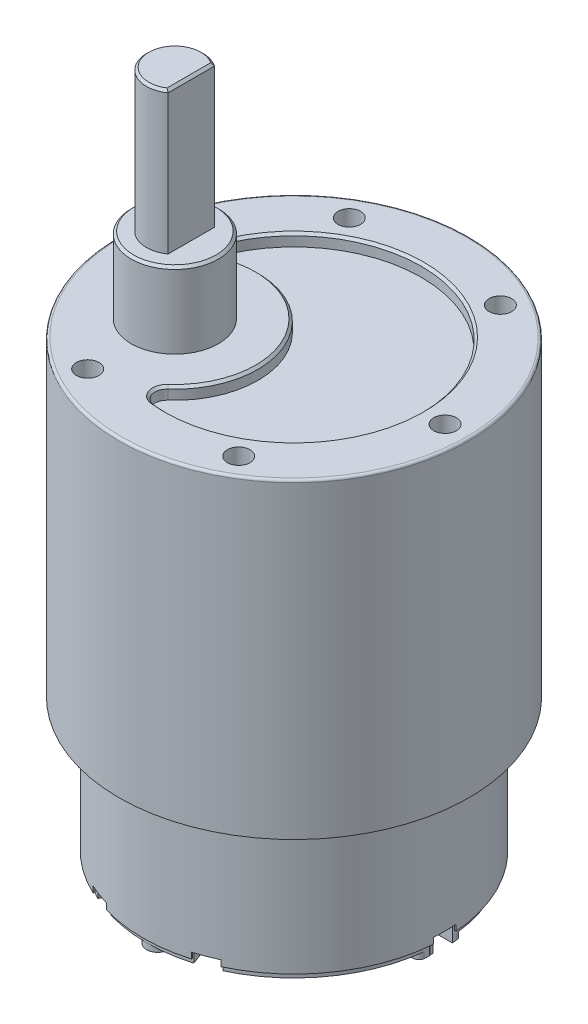
SolidWorks part; units mm, degrees
ref_plane "Front Plane" through (0, 0, 0) normal (0, 0, 1) x (1, 0, 0)
ref_plane "Top Plane" through (0, 0, 0) normal (0, 1, 0) x (1, 0, 0)
ref_plane "Right Plane" through (0, 0, 0) normal (1, 0, 0) x (0, 0, -1)
sketch "Sketch1" plane through (0, 0, 0) normal (0, 1, 0) x (1, 0, 0)
  circle A0 centre (0, 0) radius 18.5
extrude "Boss-Extrude1" add sketch "Sketch1" along normal blind 47
sketch "Sketch2" plane through (0, 0, 0) normal (0, -1, 0) x (1, 0, 0)
  circle A0 centre (0, 0) radius 15.9723
extrude "Cut-Extrude1" cut sketch "Sketch2" against normal blind 14.1 flip side to cut
sketch "Sketch3" plane through (0, 47, 0) normal (0, 1, 0) x (1, 0, 0)
  line L0 (0, 0) -> (0, 50000) construction
  line L1 (0, 0) -> (-50000, 0) construction
  circle A0 centre (-7.98, 13.8218) radius 1.1938
  circle A1 centre (-15.96, 0) radius 1.1938
  circle A2 centre (0, 0) radius 15.96
  circle A3 centre (0, 0) radius 15.96 construction
  circle A4 centre (7.98, 13.8218) radius 1.1938
  circle A5 centre (15.96, 0) radius 1.1938
  circle A6 centre (7.98, -13.8218) radius 1.1938
  circle A7 centre (-7.98, -13.8218) radius 1.1938
  point P21 (0, 0)
  dimension "D2" = 6
  dimension "D1" = 2.54
sketch "Sketch4" plane through (0, 47, 0) normal (0, 1, 0) x (1, 0, 0)
  line L0 (-7.98, 13.8218) -> (-7.98, -13.8218) construction
  line L1 (-15.96, 0) -> (-7.98, -13.8218) construction
  line L2 (-11.97, -6.9109) -> (17.6689, 10.2011) construction
  circle A0 centre (-7.98, -4.6073) radius 4.6073
extrude "Boss-Extrude2" add sketch "Sketch4" along normal blind 8
sketch "Sketch5" plane through (0, 55, 0) normal (0, 1, 0) x (1, 0, 0)
  circle A0 centre (-7.98, -4.6073) radius 3
  circle A2 centre (-7.98, -4.6073) radius 4.6073 construction
extrude "Boss-Extrude3" add sketch "Sketch5" along normal blind 15
sketch "Sketch6" plane through (0, 70, 0) normal (0, 1, 0) x (1, 0, 0)
  line L0 (-6.2443, -2.1603) -> (-6.2443, -7.0542)
  circle A0 centre (-7.98, -4.6073) radius 3 construction
  arc A1 (-6.2443, -2.1603) -> (-6.2443, -7.0542) centre (-7.98, -4.6073) ccw
extrude "Cut-Extrude3" cut sketch "Sketch6" against normal blind 15 flip side to cut
sketch "Sketch8" plane through (0, 47, 0) normal (0, 1, 0) x (1, 0, 0)
  arc A0 (-2.1427, -11.1701) -> (-10.7449, 3.7295) centre (-7.98, -4.6073) ccw
  arc A1 (-1.4339, -13.3818) -> (-12.306, 5.4491) centre (0, 0) ccw
  arc A2 (-2.1427, -11.1701) -> (-1.4339, -13.3818) centre (-1.2986, -12.1191) ccw
  arc A3 (-12.306, 5.4491) -> (-10.7449, 3.7295) centre (-11.1447, 4.9349) ccw
  dimension "D1" = 1.27
extrude "Cut-Extrude4" cut sketch "Sketch8" against normal blind 1.27
chamfer "Chamfer2" distance 0.254 angle 45 4 edges at (11.6554, 47, -6.7292) (-12.0851, 47, -4.0813) (-0.3735, 47, 0.2156) (-2.508, 47, 12.5066)
chamfer "Chamfer3" distance 0.254 angle 45 3 edges at (-6.2443, 70, 4.6073) (-10.98, 70, 4.6073) (-7.98, 55, 9.2145)
fillet "Fillet1" radius 0.254 1 edges at (0, 47, 18.5)
sketch "Sketch9" plane through (0, 14.1, 0) normal (0, -1, 0) x (1, 0, 0)
  circle A2 centre (0, 0) radius 15.9723 construction
  circle A3 centre (0, 0) radius 15.9723
  circle A4 centre (0, 0) radius 18.373
  circle M1 centre (0, 0) radius 15.9723
extrude "Cut-Extrude5" cut sketch "Sketch9" against normal blind 0.254 contours A4 M1
sketch "Sketch10" plane through (0, 0, 0) normal (0, -1, 0) x (1, 0, 0)
  circle A2 centre (0, 0) radius 15.833
extrude "Cut-Extrude6" cut sketch "Sketch10" against normal blind 0.635
sketch "Sketch11" plane through (0, 0, 0) normal (0, -1, 0) x (1, 0, 0)
  line L1 (-20.0696, 1.1938) -> (-1.727, 1.1938)
  line L2 (20.0696, -1.1938) -> (1.727, -1.1938)
  line L7 (5.974, 19.1971) -> (0, 3.3789)
  line L8 (8.2076, 18.3535) -> (1.727, 1.1938)
  line L9 (-8.2076, 18.3535) -> (-1.727, 1.1938)
  line L10 (-5.974, 19.1971) -> (0, 3.3789)
  line L13 (1.727, -1.1938) -> (8.2076, -18.3535)
  line L15 (-1.727, -1.1938) -> (-8.2076, -18.3535)
  line L19 (0, -3.3789) -> (5.974, -19.1971)
  line L21 (1.727, 1.1938) -> (20.0696, 1.1938)
  line L22 (-1.727, -1.1938) -> (-20.0696, -1.1938)
  line L23 (0, -3.3789) -> (-5.974, -19.1971)
  arc A5 (-8.2076, -18.3535) -> (-5.974, -19.1971) centre (0, 0) ccw
  arc A6 (5.974, -19.1971) -> (8.2076, -18.3535) centre (0, 0) ccw
  arc A7 (20.0696, -1.1938) -> (20.0696, 1.1938) centre (0, 0) ccw
  arc A8 (8.2076, 18.3535) -> (5.974, 19.1971) centre (0, 0) ccw
  arc A9 (-5.974, 19.1971) -> (-8.2076, 18.3535) centre (0, 0) ccw
  arc A11 (-20.0696, 1.1938) -> (-20.0696, -1.1938) centre (0, 0) ccw
extrude "Cut-Extrude7" cut sketch "Sketch11" against normal blind 0.635
sketch "Sketch13" plane through (0, 0.635, 0) normal (0, -1, 0) x (1, 0, 0)
  circle A0 centre (0, 0) radius 15.579
extrude "Boss-Extrude5" add sketch "Sketch13" along normal blind 1.27
sketch "Sketch14" plane through (0, -0.635, 0) normal (0, -1, 0) x (1, 0, 0)
  line L0 (-8.2076, 18.3535) -> (-1.727, 1.1938) construction
  line L1 (-20.0696, 1.1938) -> (-1.727, 1.1938) construction
  line L2 (-1.727, -1.1938) -> (-20.0696, -1.1938) construction
  line L3 (-1.727, -1.1938) -> (-8.2076, -18.3535) construction
  line L4 (0, -3.3789) -> (-5.974, -19.1971) construction
  line L5 (0, -3.3789) -> (5.974, -19.1971) construction
  line L6 (1.727, -1.1938) -> (8.2076, -18.3535) construction
  line L7 (20.0696, -1.1938) -> (1.727, -1.1938) construction
  line L8 (1.727, 1.1938) -> (20.0696, 1.1938) construction
  line L9 (8.2076, 18.3535) -> (1.727, 1.1938) construction
  line L10 (5.974, 19.1971) -> (0, 3.3789) construction
  line L11 (-5.974, 19.1971) -> (0, 3.3789) construction
  line L12 (-8.2076, 18.3535) -> (-6.0277, 12.5814)
  line L13 (-20.0696, 1.1938) -> (-13.8996, 1.1938)
  line L14 (-13.8996, -1.1938) -> (-20.0696, -1.1938)
  line L15 (-6.0277, -12.5814) -> (-8.2076, -18.3535)
  line L16 (-3.794, -13.425) -> (-5.974, -19.1971)
  line L17 (3.794, -13.425) -> (5.974, -19.1971)
  line L18 (6.0277, -12.5814) -> (8.2076, -18.3535)
  line L19 (20.0696, -1.1938) -> (13.8996, -1.1938)
  line L20 (13.8996, 1.1938) -> (20.0696, 1.1938)
  line L21 (8.2076, 18.3535) -> (6.0277, 12.5814)
  line L22 (5.974, 19.1971) -> (3.794, 13.425)
  line L23 (-5.974, 19.1971) -> (-3.794, 13.425)
  arc A0 (-13.8996, -1.1938) -> (-6.0277, -12.5814) centre (0, 0) ccw
  arc A1 (-20.0696, 1.1938) -> (-20.0696, -1.1938) centre (0, 0) ccw construction
  arc A2 (-8.2076, -18.3535) -> (-5.974, -19.1971) centre (0, 0) ccw construction
  arc A3 (5.974, -19.1971) -> (8.2076, -18.3535) centre (0, 0) ccw construction
  arc A4 (20.0696, -1.1938) -> (20.0696, 1.1938) centre (0, 0) ccw construction
  arc A5 (8.2076, 18.3535) -> (5.974, 19.1971) centre (0, 0) ccw construction
  arc A6 (-5.974, 19.1971) -> (-8.2076, 18.3535) centre (0, 0) ccw construction
  arc A7 (-20.0696, 1.1938) -> (-20.0696, -1.1938) centre (0, 0) ccw
  arc A8 (-8.2076, -18.3535) -> (-5.974, -19.1971) centre (0, 0) ccw
  arc A9 (5.974, -19.1971) -> (8.2076, -18.3535) centre (0, 0) ccw
  arc A10 (20.0696, -1.1938) -> (20.0696, 1.1938) centre (0, 0) ccw
  arc A11 (8.2076, 18.3535) -> (5.974, 19.1971) centre (0, 0) ccw
  arc A12 (-5.974, 19.1971) -> (-8.2076, 18.3535) centre (0, 0) ccw
  arc A13 (-6.0277, 12.5814) -> (-13.8996, 1.1938) centre (0, 0) ccw
  arc A14 (3.794, 13.425) -> (-3.794, 13.425) centre (0, 0) ccw
  arc A15 (13.8996, 1.1938) -> (6.0277, 12.5814) centre (0, 0) ccw
  arc A16 (6.0277, -12.5814) -> (13.8996, -1.1938) centre (0, 0) ccw
  arc A17 (-3.794, -13.425) -> (3.794, -13.425) centre (0, 0) ccw
extrude "Cut-Extrude8" cut sketch "Sketch14" against normal blind 1.27
sketch "Sketch15" plane through (0, 0.635, 0) normal (0, -1, 0) x (1, 0, 0)
  circle A0 centre (0, 0) radius 9.6074
extrude "Boss-Extrude6" add sketch "Sketch15" along normal blind 0.762
sketch "Sketch16" plane through (0, 0.635, 0) normal (0, -1, 0) x (1, 0, 0)
  line L0 (-15.4098, 2.2899) -> (-2.3889, 2.2899)
  line L1 (2.3889, 2.2899) -> (15.4098, 2.2899)
  line L2 (-15.5332, 1.1938) -> (-13.8659, 1.1938)
  line L3 (-15.4098, -2.2899) -> (-2.3889, -2.2899)
  line L4 (-1.1805, 14.3985) -> (-1.1805, 3.0915)
  line L5 (1.1805, -3.0915) -> (1.1805, -14.3985)
  line L6 (-20.0696, 1.1938) -> (-1.727, 1.1938) construction
  line L7 (1.1805, 14.3985) -> (1.1805, 3.0915)
  line L8 (-1.1805, -3.0915) -> (-1.1805, -14.3985)
  line L9 (2.3889, -2.2899) -> (15.4098, -2.2899)
  line L10 (-13.8659, 1.1938) -> (-13.8996, -1.1938)
  line L11 (-1.727, -1.1938) -> (-20.0696, -1.1938) construction
  line L12 (-13.8996, -1.1938) -> (-15.5332, -1.1938)
  line L13 (15.5332, 1.1938) -> (13.8211, 1.1938)
  line L14 (1.727, 1.1938) -> (20.0696, 1.1938) construction
  line L15 (13.8211, 1.1938) -> (13.8211, -1.1938)
  line L16 (20.0696, -1.1938) -> (1.727, -1.1938) construction
  line L17 (13.8211, -1.1938) -> (15.5332, -1.1938)
  circle A0 centre (0, 0) radius 15.579 construction
  arc A1 (-15.5332, -1.1938) -> (-15.4098, -2.2899) centre (0, 0) ccw
  arc A2 (-1.1805, 3.0915) -> (-2.3889, 2.2899) centre (0, 0) ccw
  arc A3 (2.3889, 2.2899) -> (1.1805, 3.0915) centre (0, 0) ccw
  arc A4 (-2.3889, -2.2899) -> (-1.1805, -3.0915) centre (0, 0) ccw
  arc A5 (1.1805, -3.0915) -> (2.3889, -2.2899) centre (0, 0) ccw
  circle A6 centre (0, 0) radius 13.9508 construction
  arc A7 (15.5332, 1.1938) -> (15.4098, 2.2899) centre (0, 0) ccw
  arc A9 (15.4098, -2.2899) -> (15.5332, -1.1938) centre (0, 0) ccw
  arc A11 (-15.4098, 2.2899) -> (-15.5332, 1.1938) centre (0, 0) ccw
  arc A12 (1.1805, 14.3985) -> (-1.1805, 14.3985) centre (0, 14.3985) ccw
  arc A13 (-1.1805, -14.3985) -> (1.1805, -14.3985) centre (0, -14.3985) ccw
extrude "Boss-Extrude7" add sketch "Sketch16" along normal blind 1.905
sketch "Sketch17" plane through (0, -1.27, 0) normal (0, -1, 0) x (1, 0, 0)
  circle A0 centre (0, 0) radius 2.54
extrude "Boss-Extrude8" add sketch "Sketch17" along normal blind 1.905
fillet "Fillet2" radius 0.635 16 edges at (1.1805, 0, 13.9007) (-1.1805, 0, 13.9007) (-13.7616, 0, -2.2899) (-1.1805, 0, -13.9007) (1.1805, 0, -13.9007) (13.7616, 0, -2.2899) (13.7616, 0, 2.2899) (-13.7616, 0, 2.2899) (-9.3305, 0.254, 2.2899) (-9.3305, 0.254, -2.2899) (-1.1805, 0.254, -9.5346) (1.1805, 0.254, -9.5346) (9.3305, 0.254, -2.2899) (9.3305, 0.254, 2.2899) (1.1805, 0.254, 9.5346) (-1.1805, 0.254, 9.5346)
fillet "Fillet3" radius 0.635 4 edges at (15.4098, -0.9525, -2.2899) (15.4098, -0.9525, 2.2899) (-15.4098, -0.9525, 2.2899) (-15.4098, -0.9525, -2.2899)
sketch "Sketch18" plane through (0, -1.27, 0) normal (0, -1, 0) x (1, 0, 0)
  line L0 (10.8985, -1.5622) -> (12.8102, -1.5622)
  line L1 (-12.8102, 1.8859) -> (-12.8102, 1.5622)
  line L5 (-10.8985, 1.8859) -> (-10.8985, 1.5622)
  line L7 (0, 0) -> (0, 50000) construction
  line L8 (12.8102, -1.5622) -> (12.8102, -1.8859)
  line L9 (10.8985, -1.5622) -> (10.8985, -1.8859)
  line L10 (-12.8102, 1.8859) -> (-10.8985, 1.8859)
  line L11 (-12.8102, 1.5622) -> (-10.8985, 1.5622)
  line L13 (12.8102, -1.8859) -> (10.8985, -1.8859)
extrude "Boss-Extrude9" add sketch "Sketch18" along normal blind 3.175
sketch "Sketch19" plane through (0, 0, 1.8859) normal (0, 0, 1) x (1, 0, 0)
  line L1 (-12.8102, -3.937) -> (-12.3022, -4.445)
  line L2 (-11.4065, -4.445) -> (-10.8985, -3.937)
  line L3 (-12.3022, -4.445) -> (-12.8102, -4.445)
  line L4 (-12.8102, -4.445) -> (-12.8102, -3.937)
  line L13 (-11.4065, -4.445) -> (-10.8985, -4.445)
  line L14 (-10.8985, -4.445) -> (-10.8985, -3.937)
  circle A0 centre (-11.8544, -3.5903) radius 0.4115
extrude "Cut-Extrude9" cut sketch "Sketch19" against normal up to next
sketch "Sketch20" plane through (0, 0, -1.5622) normal (0, 0, 1) x (1, 0, 0)
  line L0 (10.8985, -3.937) -> (11.4065, -4.445)
  line L1 (12.3022, -4.445) -> (12.8102, -3.937)
  line L3 (10.8985, -3.937) -> (10.8985, -4.445)
  line L12 (10.8985, -4.445) -> (11.4065, -4.445)
  line L13 (12.3022, -4.445) -> (12.8102, -4.445)
  line L14 (12.8102, -4.445) -> (12.8102, -3.937)
  circle A0 centre (11.8544, -3.543) radius 0.394
extrude "Cut-Extrude10" cut sketch "Sketch20" against normal up to next
extrude "Cut-Extrude11" cut sketch "Sketch3" against normal blind 3.175
